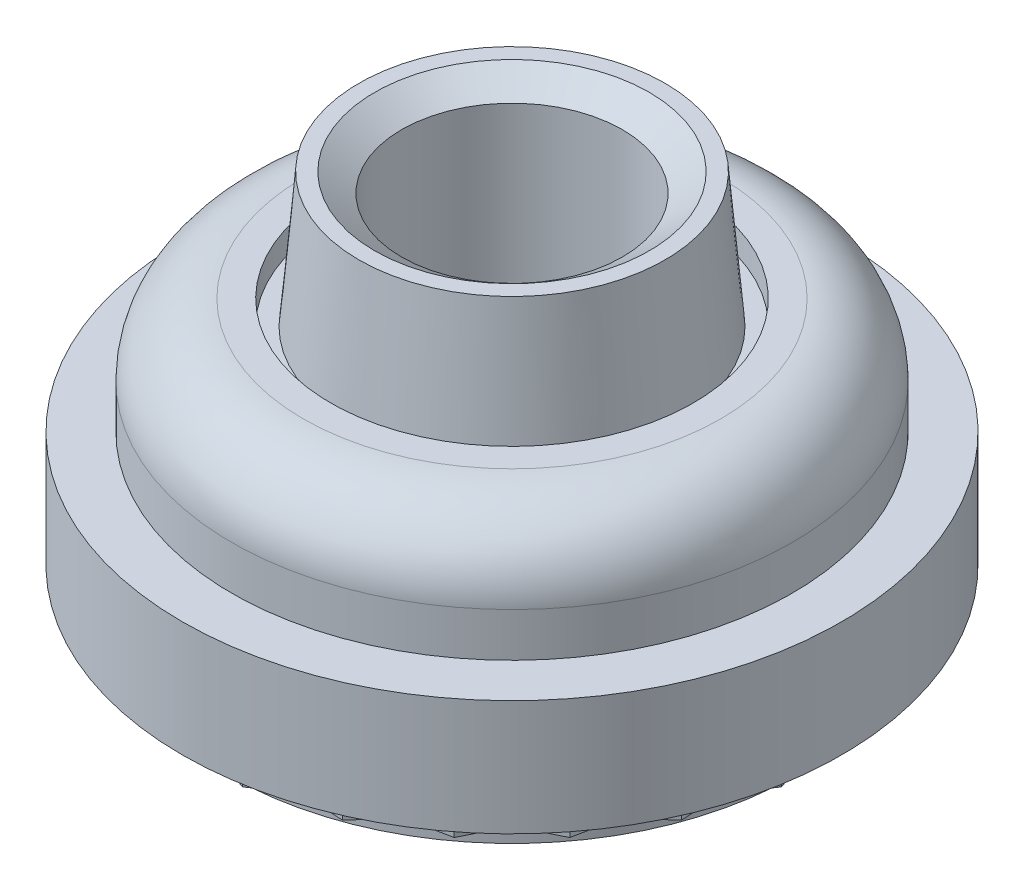
SolidWorks part; units mm, degrees
revolve "Body" add sketch "BodySke"
sketch "BodySke" plane through (0, 0, 0) normal (0, 0, 1) x (1, 0, 0)
  line L0 (6.3049, 0) -> (7.62, 0)
  line L1 (7.62, 0) -> (7.62, 2.667)
  line L2 (3.5389, 7.874) -> (2.5527, 7.874)
  line L3 (2.5527, 7.874) -> (2.5527, -0.9652)
  line L4 (2.5527, -0.9652) -> (6.5278, -0.9652)
  line L5 (6.5278, -0.9652) -> (6.5278, -0.7722)
  line L6 (6.5278, -0.7722) -> (6.3049, -0.3861)
  line L7 (1.016, 1.27) -> (3.6522, 1.27) construction
  line L9 (0, 0) -> (0, 15.24) construction
  line L10 (6.3049, -0.3861) -> (6.3049, 0)
  line L11 (3.81, 4.7752) -> (4.191, 4.7752)
  line L12 (4.191, 4.7752) -> (4.191, 5.334)
  line L13 (4.191, 5.334) -> (4.826, 5.334)
  line L14 (7.62, 2.667) -> (6.477, 2.667)
  line L15 (6.477, 2.667) -> (6.477, 3.683)
  line L16 (3.81, 4.7752) -> (3.5389, 7.874)
  arc A0 (6.477, 3.683) -> (4.826, 5.334) centre (4.826, 3.683) ccw
  dimension "E_dia" = 15.24
  dimension "C_dia" = 13.0556
  dimension "A_ht" = 0.9652
  dimension "Thread_min" = 5.1054
  dimension "C_len" = 0.193
  dimension "Clinching_ht" = 0.3861
  dimension "D1" = 60
  dimension "Advance" = 1.27
  dimension "T2_ht" = 7.874
  dimension "Guide_dia" = 8.382
  dimension "Top_flat_wid" = 0.635
  dimension "T1_ht" = 5.334
  dimension "T2_nl_lim" = 4.7752
  dimension "D_dia" = 12.954
  dimension "Shoulder_ht" = 2.667
  dimension "Nose_dia" = 7.62
  dimension "Nose_ang" = 175
cosmetic thread "ThreadCosmetic" [suppressed]
revolve "EndChamfer" cut sketch "EndChamferSke" angle 360 about L0
sketch "EndChamferSke" plane through (0, 0, 0) normal (0, 0, 1) x (1, 0, 0)
  line L0 (0, -2.54) -> (0, 7.62) construction
  line L1 (0, 0) -> (0, 15.24) construction
  line L2 (3.175, -1.2192) -> (3.175, -0.9627)
  line L3 (3.175, -0.9627) -> (2.5527, -0.5271)
  line L4 (2.5527, -0.5271) -> (2.5527, -1.2192)
  line L5 (2.5527, -1.2192) -> (3.175, -1.2192)
  line L6 (3.175, 7.874) -> (2.5527, 7.4384)
  line L8 (2.5527, 7.4384) -> (2.5527, 7.874)
  line L9 (3.175, 7.874) -> (2.5527, 7.874)
  line L10 (2.5527, 7.874) -> (-2.5527, 7.874) construction
  line L11 (-6.5278, -0.9652) -> (6.5278, -0.9652) construction
  dimension "D1" = 0.254
  dimension "Thread_nominal" = 6.35
  dimension "D2" = 34.99
  dimension "Thread_min" = 5.1054
  dimension "Inset" = 0.0025
ref_plane "Plane1" through (0, 0, 0) normal (0, 0, 1) x (1, 0, 0)
ref_plane "Plane2" through (0, 0, 0) normal (0, 1, 0) x (1, 0, 0)
ref_plane "Plane3" through (0, 0, 0) normal (1, 0, 0) x (0, 0, -1)
sketch "CliRinSegSke" plane through (0, 0, 0) normal (0, -1, 0) x (1, 0, 0)
  line L0 (0, 0) -> (0, 7.62) construction
  line L1 (0.9449, 7.1771) -> (0, 6.858)
  line L2 (0, 6.858) -> (-0.9449, 7.1771)
  line L3 (-0.9449, 7.1771) -> (-0.9165, 6.9618)
  line L4 (-0.9165, 6.9618) -> (0, 6.6523)
  line L5 (0, 6.6523) -> (0.9165, 6.9618)
  line L6 (0.9165, 6.9618) -> (0.9449, 7.1771)
  circle A0 centre (0, 0) radius 7.239 construction
  circle A1 centre (0, 0) radius 6.858 construction
  circle A2 centre (0, 0) radius 6.6523 construction
  circle A3 centre (0, 0) radius 7.0218 construction
  circle A4 centre (0, 0) radius 6.5278 construction
  dimension "Angle" = 15
  dimension "D2" = 14.0437
  dimension "D3" = 13.716
  dimension "D4" = 13.3045
  dimension "D1" = 14.478
ref_plane "Plane4" through (0, -0.5486, 0) normal (0, 1, 0) x (-1, 0, 0)
sketch "ThdSchSke" plane through (0, 0, 0) normal (0, 0, 1) x (1, 0, 0)
  line L0 (0, -5.08) -> (0, 7.62) construction
  line L1 (0, 0) -> (0, 15.24) construction
  line L2 (0, -0.9627) -> (3.175, -0.9627) construction
  line L4 (3.175, -0.9627) -> (2.5527, -0.5269)
  line L6 (3.175, -0.9627) -> (2.5527, -1.3984)
  line L7 (2.5527, -0.5269) -> (2.5527, -1.3984)
  line L8 (3.175, -0.9627) -> (-3.175, -0.9627) construction
  dimension "Thread_min" = 5.1054
  dimension "Thread_nominal" = 6.35
revolve "ThreadSchematic" [suppressed] cut sketch "ThdSchSke" angle 360 about L0
pattern_linear "ThdSchPat" [suppressed]
extrude "ClinchingRingSegment" add sketch "CliRinSegSke" along normal blind 0.3861
pattern_circular "ClinchingRing" count 24 every 15 about axis through (0, 0, 0) along (0, 1, 0) of "ClinchingRingSegment"
sketch "SqrCutSke" plane through (0, -0.9652, 0) normal (0, -1, 0) x (1, 0, 0)
  line L0 (3.81, -3.556) -> (3.81, 3.556)
  line L1 (3.556, 3.81) -> (-3.556, 3.81)
  line L2 (-3.81, 3.556) -> (-3.81, -3.556)
  line L3 (-3.556, -3.81) -> (3.556, -3.81)
  line L4 (-3.556, -4.191) -> (3.556, -4.191)
  line L5 (-4.191, 3.556) -> (-4.191, -3.556)
  line L6 (3.556, 4.191) -> (-3.556, 4.191)
  line L7 (4.191, -3.556) -> (4.191, 3.556)
  circle A0 centre (0, 0) radius 3.81 construction
  circle A1 centre (0, 0) radius 3.81 construction
  circle A4 centre (0, 0) radius 5.3882 construction
  arc A6 (-3.81, 3.556) -> (-3.556, 3.81) centre (-3.556, 3.556) cw
  arc A7 (3.81, 3.556) -> (3.556, 3.81) centre (3.556, 3.556) ccw
  arc A8 (3.556, -3.81) -> (3.81, -3.556) centre (3.556, -3.556) ccw
  arc A9 (-3.81, -3.556) -> (-3.556, -3.81) centre (-3.556, -3.556) ccw
  arc A10 (-4.191, -3.556) -> (-3.556, -4.191) centre (-3.556, -3.556) ccw
  arc A11 (-4.191, 3.556) -> (-3.556, 4.191) centre (-3.556, 3.556) cw
  arc A12 (4.191, 3.556) -> (3.556, 4.191) centre (3.556, 3.556) ccw
  arc A13 (3.556, -4.191) -> (4.191, -3.556) centre (3.556, -3.556) ccw
  point P12 (-3.81, 3.81)
  point P15 (3.81, 3.81)
  point P18 (3.81, -3.81)
  point P21 (-3.81, -3.81)
  dimension "D1" = 0.254
  dimension "D2" = 0.381
extrude "SqrCut" cut sketch "SqrCutSke" against normal blind 0.9652
equation "' \"A_ht@BodySke\" = 0.038"
equation "' \"C_dia@BodySke\" = 0.514"
equation "' \"D_dia@BodySke\" = 0.51"
equation "' \"E_dia@BodySke\" = 0.6"
equation "' \"T1_ht@BodySke\" = 0.21"
equation "' \"T2_ht@BodySke\" = 0.31"
equation "' \"Advance@BodySke\" = 0.05"
equation "' \"Thread_min@BodySke\" = 0.201"
equation "' \"Thread_nominal@ThreadCosmetic\" = 0.25"
equation "' \"Nose_ang@BodySke\" = 175"
equation "' \"T2_ht@BodySke\" =  \"T1_ht@BodySke\" * 0.9 ' make NL"
equation "' \"T2_ht@BodySke\" = \"T1_ht@BodySke\" * 0.9 ' make NL"
equation "\"Nose_dia@BodySke\" = \"Thread_nominal@ThreadCosmetic\" * 1.2"
equation "\"Top_flat_wid@BodySke\" = \"Thread_nominal@ThreadCosmetic\" * 0.1"
equation "\"Guide_dia@BodySke\" = \"Nose_dia@BodySke\" + 0.03"
equation "\"T2_nl_lim@BodySke\" = \"T1_ht@BodySke\" * 0.9 - 0.001"
equation "\"Shoulder_ht@BodySke\" = \"T1_ht@BodySke\" * 0.5"
equation "\"Depth@SqrCut\" = \"A_ht@BodySke\""
equation "\"Count@ClinchingRing\" = 24"
equation "\"Angle@ClinchingRing\" = 360 / \"Count@ClinchingRing\""
equation "\"Angle@CliRinSegSke\" = 360 / \"Count@ClinchingRing\""
equation "\"D1@CliRinSegSke\" = \"E_dia@BodySke\" * 0.95"
equation "\"D2@CliRinSegSke\" = \"D1@CliRinSegSke\" * 0.97"
equation "\"D3@CliRinSegSke\" = \"E_dia@BodySke\" * 0.9"
equation "\"D4@CliRinSegSke\" = \"D3@CliRinSegSke\" * 0.97"
equation "\"C_len@BodySke\" = \"A_ht@BodySke\" * 0.2"
equation "\"Clinching_ht@BodySke\" = \"A_ht@BodySke\" * 0.4"
equation "\"Clinching_ht@ClinchingRingSegment\" =  \"A_ht@BodySke\" * 0.4"
equation "\"Thread_nominal@EndChamferSke\" = \"Thread_nominal@ThreadCosmetic\""
equation "\"Thread_min@EndChamferSke\" = \"Thread_min@BodySke\""
equation "\"D2@EndChamferSke\" = \"Vee_angle@ThdSchSke\" / 2 - 0.01"
equation "\"Thread_nominal@ThdSchSke\" = \"Thread_nominal@ThreadCosmetic\""
equation "\"Thread_min@ThdSchSke\" = \"Thread_min@BodySke\""
equation "\"Num_threads@ThdSchPat\" = int(  ( \"A_ht@BodySke\" + \"T2_ht@BodySke\" - \"Inset@EndChamferSke\" ) / \"Advance@BodySke\" + 0.999 )  + 1"
equation "\"Advance@ThdSchPat\" = (  \"A_ht@BodySke\" + \"T2_ht@BodySke\" - \"Inset@EndChamferSke\"  ) /  (\"Num_threads@ThdSchPat\" - 1) 'relax it"
